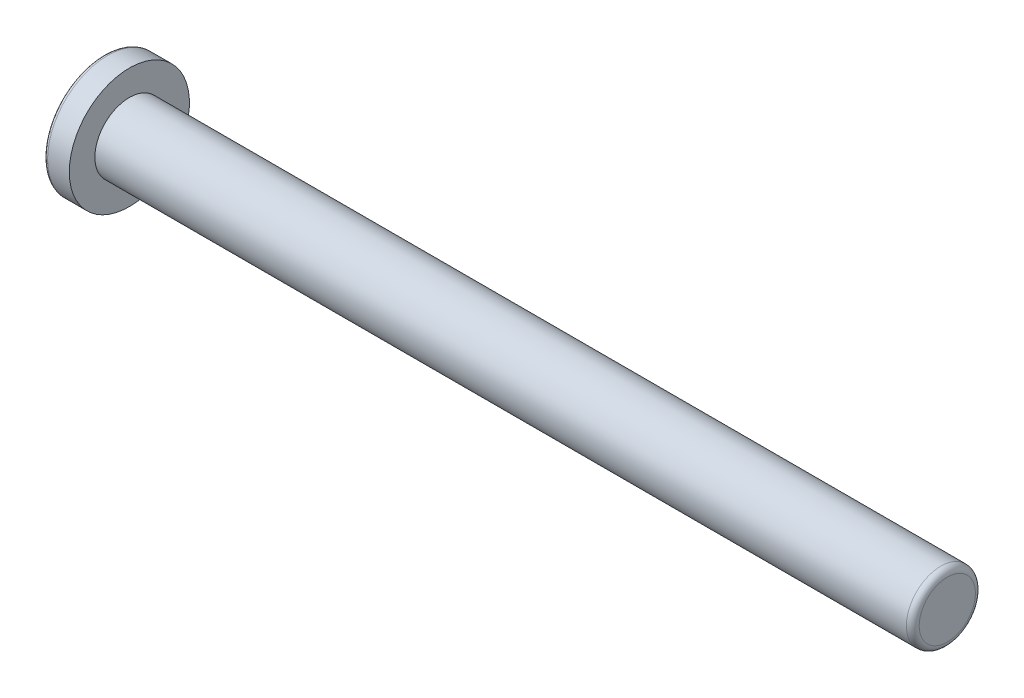
SolidWorks part; units mm, degrees
material "1060 Alloy"
ref_plane "Front Plane" through (0, 0, 0) normal (0, 0, 1) x (1, 0, 0)
ref_plane "Top Plane" through (0, 0, 0) normal (0, 1, 0) x (1, 0, 0)
ref_plane "Right Plane" through (0, 0, 0) normal (1, 0, 0) x (0, 0, -1)
other "Configuration Table"
sketch "Sketch1" plane through (0, 0, 0) normal (0, 0, 1) x (1, 0, 0)
  line L0 (0, 0) -> (0, 27)
  line L1 (0, 27) -> (-640, 27)
  line L2 (-640, 27) -> (-640, 47)
  line L3 (-640, 47) -> (-660, 47)
  line L4 (-660, 47) -> (-660, 0)
  line L5 (-660, 0) -> (10.8676, 0) construction
  line L6 (0, 0) -> (-660, 0)
revolve "Revolve1" add sketch "Sketch1" angle 360 about L5
fillet "Fillet1" radius 3 1 edges at (-660, 0, 47)
fillet "Fillet2" radius 5 1 edges at (0, 0, 27)
